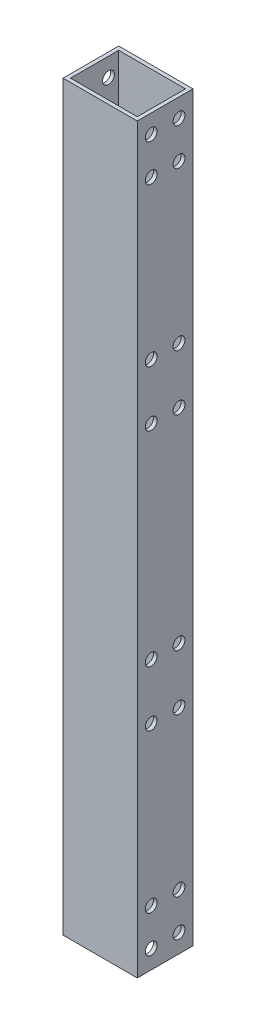
SolidWorks part; units mm, degrees
ref_plane "前视基准面" through (0, 0, 0) normal (0, 0, 1) x (1, 0, 0)
ref_plane "上视基准面" through (0, 0, 0) normal (0, 1, 0) x (1, 0, 0)
ref_plane "右视基准面" through (0, 0, 0) normal (1, 0, 0) x (0, 0, -1)
other "Configuration Table"
sketch "草图1" plane through (0, 0, 0) normal (0, 1, 0) x (1, 0, 0)
  line L1 (-10, -7.5) -> (10, -7.5)
  line L2 (-10, -7.5) -> (-10, 7.5)
  line L3 (-10, 7.5) -> (10, 7.5)
  line L4 (10, -7.5) -> (10, 7.5)
  line L5 (-10, -7.5) -> (10, 7.5) construction
  line L6 (-10, 7.5) -> (10, -7.5) construction
  point P0 (0, 0)
  dimension "D1" = 20
  dimension "D2" = 15
extrude "拉伸-薄壁1" add sketch "草图1" along normal blind 200 thin thin type one direction reverse wall 1
sketch "草图2" plane through (10, 0, 0) normal (1, 0, 0) x (0, 0, -1)
  line L0 (7.5, 200) -> (7.5, 0) construction
  line L1 (-7.5, 200) -> (7.5, 200)
  line L2 (-7.5, 200) -> (-7.5, 180)
  line L3 (-7.5, 180) -> (7.5, 180)
  line L4 (7.5, 200) -> (7.5, 180)
  line L6 (-7.5, 0) -> (7.5, 0)
  line L7 (-7.5, 0) -> (-7.5, 20)
  line L8 (-7.5, 20) -> (7.5, 20)
  line L9 (7.5, 0) -> (7.5, 20)
  dimension "D1" = 20
  dimension "D2" = 20
sketch "草图3" plane through (10, 0, 0) normal (1, 0, 0) x (0, 0, -1)
  line L0 (-7.5, 100) -> (7.5, 100) construction
  line L1 (-7.5, 200) -> (-7.5, 0) construction
  line L2 (7.5, 200) -> (7.5, 0) construction
  line L3 (0, 375) -> (0, 394.0699) construction
  line L4 (-7.5, 135) -> (7.5, 135) construction
  circle A0 centre (-3.75, 142.5) radius 1.6
  circle A1 centre (-3.75, 127.5) radius 1.6
  circle A2 centre (3.75, 127.5) radius 1.6
  circle A3 centre (3.75, 142.5) radius 1.6
  circle A4 centre (-3.75, 72.5) radius 1.6
  circle A5 centre (3.75, 72.5) radius 1.6
  circle A6 centre (3.75, 57.5) radius 1.6
  circle A7 centre (-3.75, 57.5) radius 1.6
  dimension "D4" = 3.2
  dimension "D1" = 35
  dimension "D2" = 3.75
  dimension "D3" = 7.5
extrude "切除-拉伸1" cut sketch "草图3" against normal through all
sketch "草图4" plane through (10, 0, 0) normal (1, 0, 0) x (0, 0, -1)
  line L0 (-7.5, 10) -> (7.5, 10) construction
  line L1 (-7.5, 0) -> (-7.5, 20) construction
  line L2 (7.5, 0) -> (7.5, 20) construction
  line L3 (0, 0) -> (0, 20) construction
  line L4 (-7.5, 20) -> (7.5, 20) construction
  line L5 (7.5, 100) -> (2.3053, 100) construction
  line L6 (7.5, 200) -> (7.5, 0) construction
  line L7 (0, 200) -> (0, 180) construction
  line L8 (-7.5, 190) -> (7.5, 190) construction
  circle A0 centre (-3.75, 5) radius 1.6
  circle A1 centre (-3.75, 15) radius 1.6
  circle A2 centre (3.75, 5) radius 1.6
  circle A3 centre (3.75, 15) radius 1.6
  circle A4 centre (3.75, 185) radius 1.6
  circle A5 centre (3.75, 195) radius 1.6
  circle A6 centre (-3.75, 185) radius 1.6
  circle A7 centre (-3.75, 195) radius 1.6
  dimension "D1" = 3.2
  dimension "D2" = 3.75
  dimension "D3" = 5
extrude "切除-拉伸2" cut sketch "草图4" against normal through all
